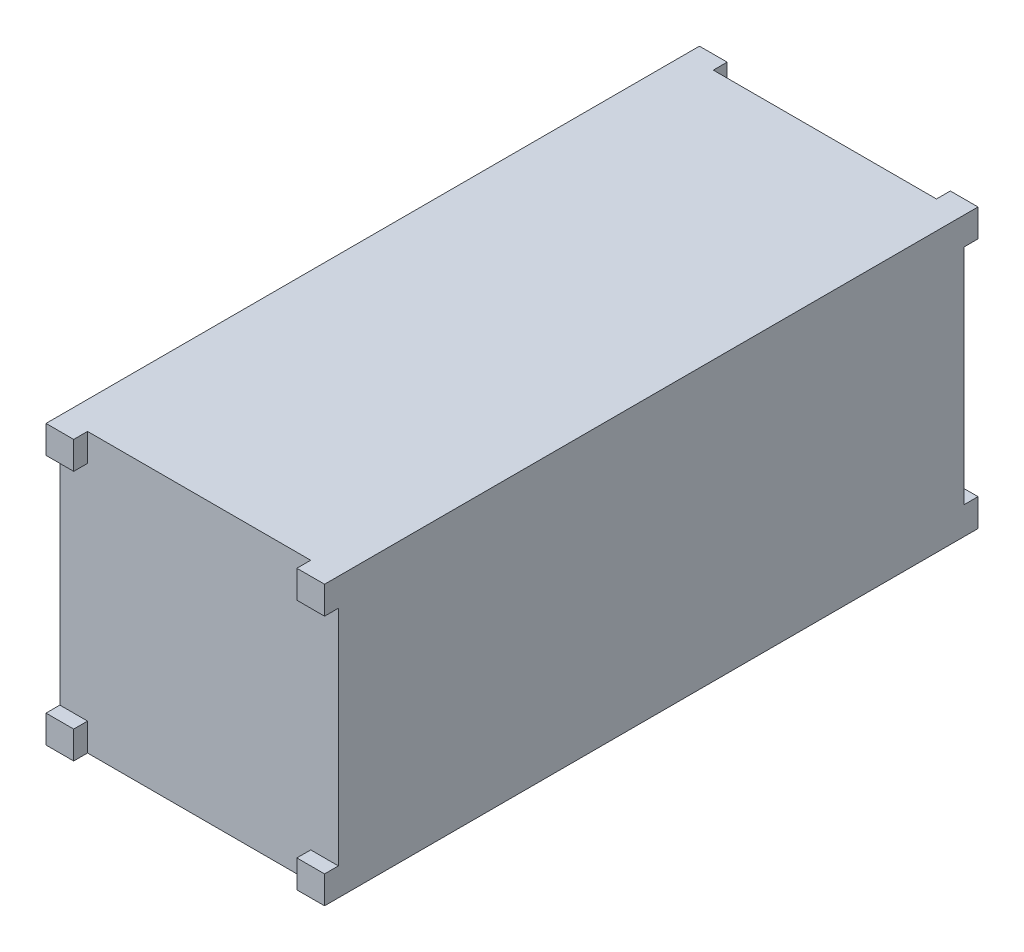
SolidWorks part; units mm, degrees
ref_plane "Front Plane" through (0, 0, 0) normal (0, 0, 1) x (1, 0, 0)
ref_plane "Top Plane" through (0, 0, 0) normal (0, 1, 0) x (1, 0, 0)
ref_plane "Right Plane" through (0, 0, 0) normal (1, 0, 0) x (0, 0, -1)
sketch "Sketch1" plane through (0, 0, 0) normal (0, 0, 1) x (1, 0, 0)
  line L1 (50.3, -50.3) -> (-50.3, -50.3)
  line L2 (50.3, -50.3) -> (50.3, 50.3)
  line L3 (50.3, 50.3) -> (-50.3, 50.3)
  line L4 (-50.3, -50.3) -> (-50.3, 50.3)
  line L5 (50.3, -50.3) -> (-50.3, 50.3) construction
  line L6 (50.3, 50.3) -> (-50.3, -50.3) construction
  point P0 (0, 0)
  dimension "D1" = 100.6
  dimension "D2" = 100.6
extrude "Boss-Extrude1" add sketch "Sketch1" along normal mid plane 226
sketch "Sketch2" plane through (0, 0, 113) normal (0, 0, 1) x (1, 0, 0)
  line L0 (0, 50.3) -> (0, -50.3) construction
  line L1 (-50.3, 50.3) -> (-40.3, 50.3)
  line L2 (-50.3, 50.3) -> (-50.3, 40.3)
  line L3 (-50.3, 40.3) -> (-40.3, 40.3)
  line L4 (-40.3, 50.3) -> (-40.3, 40.3)
  line L5 (50.3, 50.3) -> (-50.3, 50.3) construction
  line L6 (-50.3, -50.3) -> (50.3, -50.3) construction
  line L7 (50.3, 40.3) -> (40.3, 40.3)
  line L8 (40.3, 50.3) -> (40.3, 40.3)
  line L9 (50.3, 50.3) -> (40.3, 50.3)
  line L10 (50.3, 50.3) -> (50.3, 40.3)
  line L11 (-50.3, 0) -> (50.3, 0) construction
  line L12 (-50.3, 50.3) -> (-50.3, -50.3) construction
  line L13 (50.3, -50.3) -> (50.3, 50.3) construction
  line L14 (50.3, -50.3) -> (50.3, -40.3)
  line L15 (50.3, -50.3) -> (40.3, -50.3)
  line L16 (40.3, -50.3) -> (40.3, -40.3)
  line L17 (50.3, -40.3) -> (40.3, -40.3)
  line L18 (-50.3, -40.3) -> (-40.3, -40.3)
  line L19 (-40.3, -50.3) -> (-40.3, -40.3)
  line L20 (-50.3, -50.3) -> (-40.3, -50.3)
  line L21 (-50.3, -50.3) -> (-50.3, -40.3)
  dimension "D1" = 10
  dimension "D2" = 10
extrude "Boss-Extrude2" add sketch "Sketch2" along normal blind 5
sketch "Sketch3" plane through (0, 0, -113) normal (0, 0, -1) x (-1, 0, 0)
  line L0 (0, 50.3) -> (0, 0) construction
  line L1 (-50.3, 50.3) -> (-40.3, 50.3)
  line L2 (-50.3, 50.3) -> (-50.3, 40.3)
  line L3 (-50.3, 40.3) -> (-40.3, 40.3)
  line L4 (-40.3, 50.3) -> (-40.3, 40.3)
  line L5 (-50.3, 50.3) -> (50.3, 50.3) construction
  line L6 (0, 0) -> (50.3, 0) construction
  line L7 (50.3, 50.3) -> (50.3, -50.3) construction
  line L8 (50.3, 40.3) -> (40.3, 40.3)
  line L9 (40.3, 50.3) -> (40.3, 40.3)
  line L10 (50.3, 50.3) -> (40.3, 50.3)
  line L11 (50.3, 50.3) -> (50.3, 40.3)
  line L12 (50.3, -50.3) -> (50.3, -40.3)
  line L13 (50.3, -50.3) -> (40.3, -50.3)
  line L14 (40.3, -50.3) -> (40.3, -40.3)
  line L15 (50.3, -40.3) -> (40.3, -40.3)
  line L16 (-50.3, -40.3) -> (-40.3, -40.3)
  line L17 (-40.3, -50.3) -> (-40.3, -40.3)
  line L18 (-50.3, -50.3) -> (-40.3, -50.3)
  line L19 (-50.3, -50.3) -> (-50.3, -40.3)
  dimension "D1" = 10
  dimension "D2" = 10
extrude "Boss-Extrude3" add sketch "Sketch3" along normal blind 5
